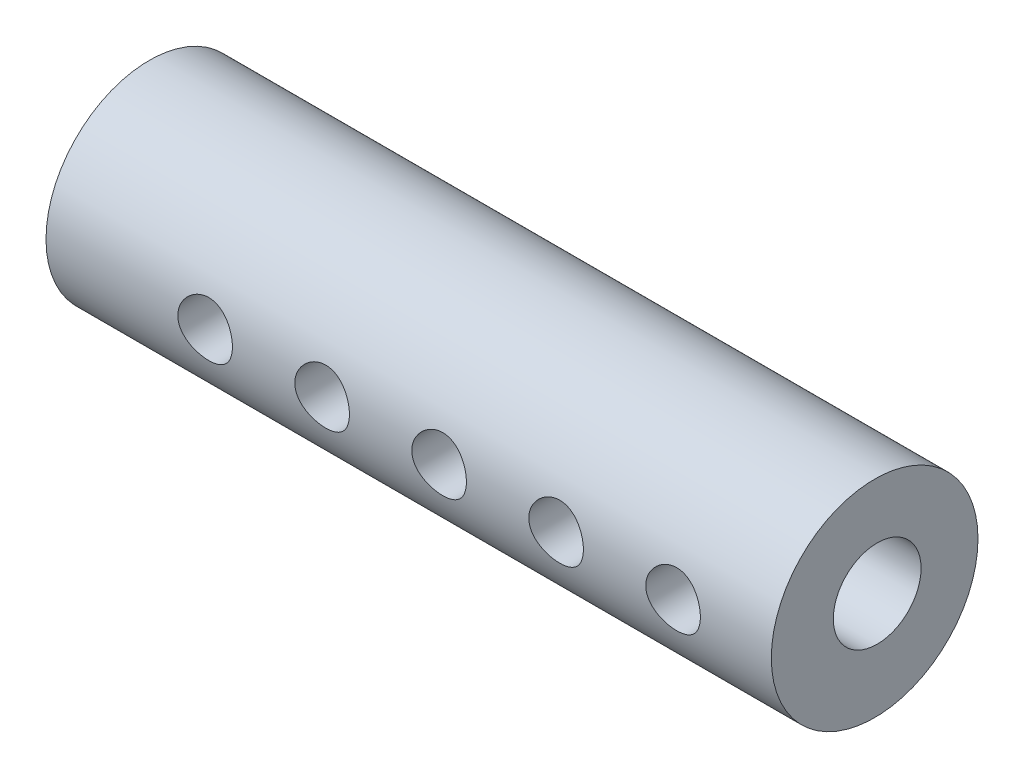
SolidWorks part; units mm, degrees
ref_plane "Front Plane" through (0, 0, 0) normal (0, 0, 1) x (1, 0, 0)
ref_plane "Top Plane" through (0, 0, 0) normal (0, 1, 0) x (1, 0, 0)
ref_plane "Right Plane" through (0, 0, 0) normal (1, 0, 0) x (0, 0, -1)
sketch "Sketch1" plane through (0, 0, 0) normal (1, 0, 0) x (0, 0, -1)
  circle A0 centre (0, 0) radius 16.8275
  dimension "D1" = 33.655
extrude "Boss-Extrude1" add sketch "Sketch1" along normal blind 118.11
sketch "Sketch2" plane through (0, 0, 0) normal (-1, 0, 0) x (0, 0, 1)
  circle A0 centre (-0.4127, 0.4763) radius 7.1438
  circle A1 centre (0, 0) radius 16.8275 construction
  dimension "D1" = 14.2875
  dimension "D2" = 17.3038
  dimension "D3" = 16.4147
extrude "Cut-Extrude1" cut sketch "Sketch2" against normal up to surface (118.11 mm away) up to face at (118.11, 0, -16.8275)
ref_plane "Plane1" through (14.478, 0, 0) normal (-1, 0, 0) x (0, 0, 1)
sketch "Sketch3" plane through (0, 0, 0) normal (-1, 0, 0) x (0, 0, 1)
  line L0 (0, 0) -> (12.8906, -10.8165)
  line L1 (0, 0) -> (16.8275, 0)
  circle A0 centre (0, 0) radius 16.8275 construction
  point P5 (16.8275, 0)
  dimension "D1" = 40
ref_plane "Plane2" through (0, 0, 16.8275) normal (0, 0, 1) x (1, 0, 0)
sketch "Sketch4" plane through (0, 0, 16.8275) normal (0, 0, 1) x (1, 0, 0)
  line L0 (14.478, 0) -> (118.11, 0) construction
  line L1 (14.478, 18.5102) -> (14.478, -18.5102) construction
  line L2 (118.11, -16.8275) -> (118.11, 16.8275) construction
  circle A0 centre (25.908, 0) radius 4.445
  dimension "D1" = 8.89
  dimension "D2" = 11.43
extrude "Cut-Extrude2" cut sketch "Sketch4" against normal up to surface (10.1124 mm away) contours A0
pattern_linear "LPattern1" count 5 spacing 19.05 along (1, 0, 0) of "Cut-Extrude2"
